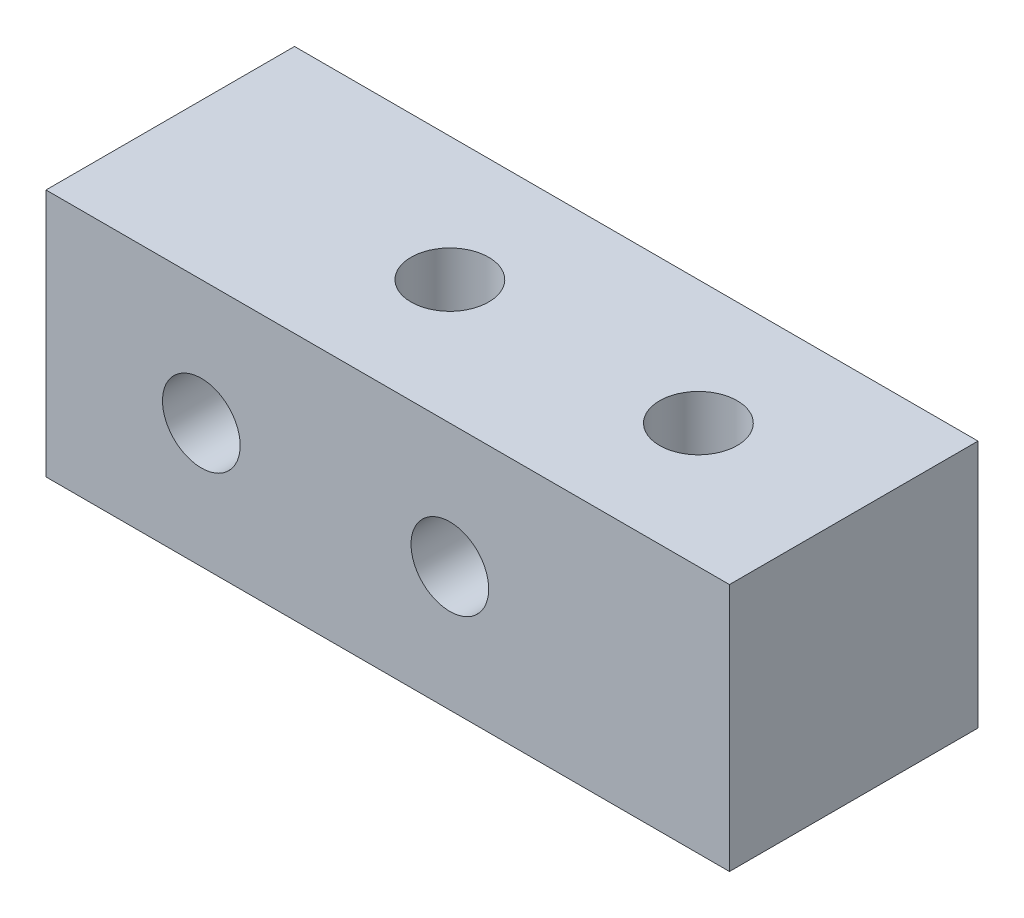
SolidWorks part; units mm, degrees
material "6061 合金"
ref_plane "前视基准面" through (0, 0, 0) normal (0, 0, 1) x (1, 0, 0)
ref_plane "上视基准面" through (0, 0, 0) normal (0, 1, 0) x (1, 0, 0)
ref_plane "右视基准面" through (0, 0, 0) normal (1, 0, 0) x (0, 0, -1)
sketch "草图2" plane through (0, 0, 0) normal (0, 0, 1) x (1, 0, 0)
  line L1 (11, -4) -> (-11, -4)
  line L2 (11, -4) -> (11, 4)
  line L3 (11, 4) -> (-11, 4)
  line L4 (-11, -4) -> (-11, 4)
  line L5 (11, -4) -> (-11, 4) construction
  line L6 (11, 4) -> (-11, -4) construction
  point P0 (0, 0)
  dimension "D1" = 22
  dimension "D2" = 8
extrude "凸台-拉伸1" add sketch "草图2" along normal blind 8
sketch "草图3" plane through (-11, 0, 0) normal (-1, 0, 0) x (0, 0, 1)
  line L0 (0, 4) -> (8, -4) construction
  line L1 (8, 4) -> (0, -4) construction
sketch "草图4" plane through (0, 0, 8) normal (0, 0, 1) x (1, 0, 0)
  line L0 (-11, 4) -> (-11, -4) construction
  point P0 (-6, 0)
  point P1 (2, 0)
  dimension "D1" = 5
  dimension "D2" = 8
sketch "草图5" plane through (0, 4, 0) normal (0, 1, 0) x (1, 0, 0)
  line L0 (11, -8) -> (11, 0) construction
  point P0 (6, -4)
  point P1 (-2, -4)
  dimension "D1" = 5
  dimension "D2" = 8
hole_wizard "M3 螺纹孔的螺纹孔钻头1" positions "3D草图1" profile "草图6" hole size "M3" standard "DIN" end condition through all
sketch3d "3D草图1"
  point P0 (-2, 4, 4)
  point P3 (6, 4, 4)
  point P6 (2, 0, 8)
  point P9 (-6, 0, 8)
sketch "草图6" plane through (-2, 4, 4) normal (1, 0, 0) x (0, 0, 1)
  line L0 (0, 0) -> (0, 8)
  line L1 (0, 8) -> (1.25, 8)
  line L2 (1.25, 8) -> (1.25, 0)
  line L5 (1.25, 0) -> (0, 0)
  line L11 (0, -6.35) -> (0, 107.95) construction
  dimension "通孔孔直径" = 2.5
  dimension "通孔孔深度" = 8
